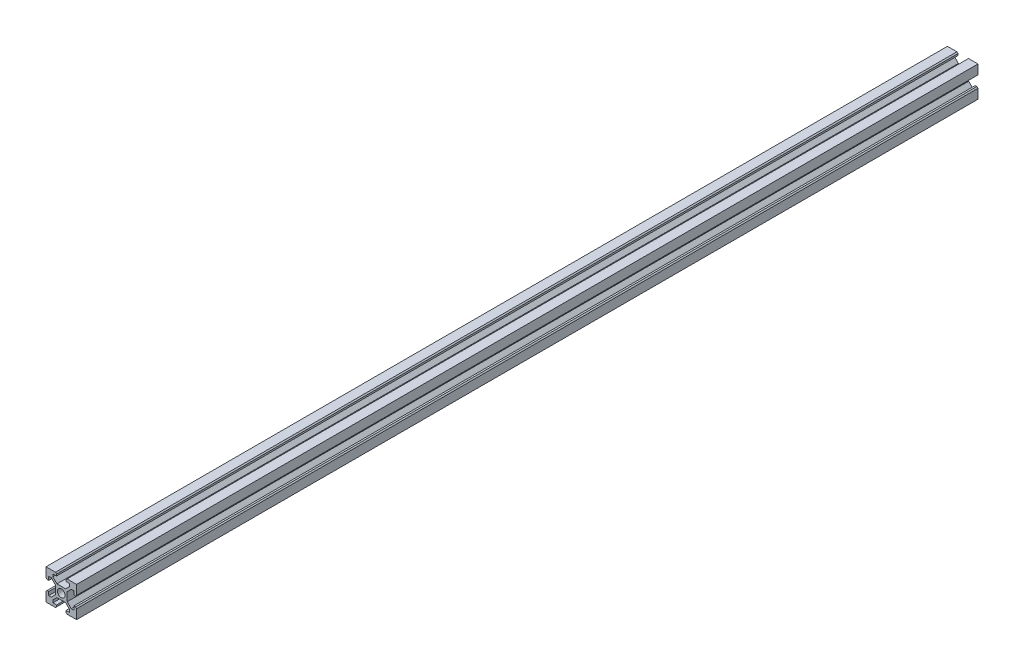
SolidWorks part; units mm, degrees
material "Cast Alloy Steel"
ref_plane "Front Plane" through (0, 0, 0) normal (0, 0, 1) x (1, 0, 0)
ref_plane "Top Plane" through (0, 0, 0) normal (0, 1, 0) x (1, 0, 0)
ref_plane "Right Plane" through (0, 0, 0) normal (1, 0, 0) x (0, 0, -1)
sketch "Sketch1" plane through (0, 0, 0) normal (0, 0, 1) x (1, 0, 0)
  line L0 (3.9, -2.8393) -> (6.5607, -5.5)
  line L1 (-10, 10) -> (10, 10) construction
  line L2 (-10, 10) -> (-10, -10) construction
  line L3 (-10, -10) -> (10, -10) construction
  line L4 (10, 10) -> (10, -10) construction
  line L5 (-10, 10) -> (10, -10) construction
  line L6 (-10, -10) -> (10, 10) construction
  line L7 (-3.9, -3.9) -> (3.9, -3.9) construction
  line L8 (-3.9, -3.9) -> (-3.9, 3.9) construction
  line L9 (-3.9, 3.9) -> (3.9, 3.9) construction
  line L10 (3.9, -3.9) -> (3.9, 3.9) construction
  line L11 (-3.9, -3.9) -> (3.9, 3.9) construction
  line L12 (-3.9, 3.9) -> (3.9, -3.9) construction
  line L13 (-10, 10) -> (-5.5, 10) construction
  line L14 (-10, 10) -> (-10, 5.5) construction
  line L15 (-10, 5.5) -> (-5.5, 5.5) construction
  line L16 (-5.5, 10) -> (-5.5, 5.5) construction
  line L17 (10, 10) -> (5.5, 10) construction
  line L18 (10, 10) -> (10, 5.5) construction
  line L19 (10, 5.5) -> (5.5, 5.5) construction
  line L20 (5.5, 10) -> (5.5, 5.5) construction
  line L21 (-10, -10) -> (-5.5, -10) construction
  line L22 (-10, -10) -> (-10, -5.5) construction
  line L23 (-10, -5.5) -> (-5.5, -5.5) construction
  line L24 (-5.5, -10) -> (-5.5, -5.5) construction
  line L25 (10, -10) -> (5.5, -10) construction
  line L26 (10, -10) -> (10, -5.5) construction
  line L27 (10, -5.5) -> (5.5, -5.5) construction
  line L28 (5.5, -10) -> (5.5, -5.5) construction
  line L29 (2.8393, -3.9) -> (5.5, -6.5607)
  line L30 (-5.5, 6.5607) -> (-2.8393, 3.9)
  line L31 (-6.5607, 5.5) -> (-3.9, 2.8393)
  line L32 (5.5, 6.5607) -> (2.8393, 3.9)
  line L33 (6.5607, 5.5) -> (3.9, 2.8393)
  line L34 (-6.5607, -5.5) -> (-3.9, -2.8393)
  line L35 (-5.5, -6.5607) -> (-2.8393, -3.9)
  line L36 (-2.8393, 3.9) -> (2.8393, 3.9)
  line L37 (-3.9, 2.8393) -> (-3.9, -2.8393)
  line L38 (-2.8393, -3.9) -> (2.8393, -3.9)
  line L39 (3.9, -2.8393) -> (3.9, 2.8393)
  line L40 (5.5, 6.5607) -> (5.5, 8.2007)
  line L41 (5.5, 8.2007) -> (3.1, 8.2007)
  line L42 (3.1, 8.2007) -> (3.1, 9.3)
  line L43 (3.1, 9.3) -> (3.8, 10)
  line L44 (3.8, 10) -> (10, 10)
  line L45 (10, 10) -> (10, 3.8)
  line L46 (10, 3.8) -> (9.3, 3.1)
  line L47 (9.3, 3.1) -> (8.2007, 3.1)
  line L48 (8.2007, 3.1) -> (8.2007, 5.5)
  line L49 (8.2007, 5.5) -> (6.5607, 5.5)
  line L50 (3.1, -8.2007) -> (5.5, -8.2007)
  line L51 (3.1, -9.3) -> (3.1, -8.2007)
  line L52 (3.8, -10) -> (3.1, -9.3)
  line L53 (10, -10) -> (3.8, -10)
  line L54 (10, -3.8) -> (10, -10)
  line L55 (9.3, -3.1) -> (10, -3.8)
  line L56 (8.2007, -3.1) -> (9.3, -3.1)
  line L57 (8.2007, -5.5) -> (8.2007, -3.1)
  line L58 (6.5607, -5.5) -> (8.2007, -5.5)
  line L59 (5.5, -8.2007) -> (5.5, -6.5607)
  line L60 (-8.2007, -3.1) -> (-8.2007, -5.5)
  line L61 (-9.3, -3.1) -> (-8.2007, -3.1)
  line L62 (-10, -3.8) -> (-9.3, -3.1)
  line L63 (-10, -10) -> (-10, -3.8)
  line L64 (-3.8, -10) -> (-10, -10)
  line L65 (-3.1, -9.3) -> (-3.8, -10)
  line L66 (-3.1, -8.2007) -> (-3.1, -9.3)
  line L67 (-5.5, -8.2007) -> (-3.1, -8.2007)
  line L68 (-5.5, -6.5607) -> (-5.5, -8.2007)
  line L69 (-8.2007, -5.5) -> (-6.5607, -5.5)
  line L70 (-3.1, 8.2007) -> (-5.5, 8.2007)
  line L71 (-3.1, 9.3) -> (-3.1, 8.2007)
  line L72 (-3.8, 10) -> (-3.1, 9.3)
  line L73 (-10, 10) -> (-3.8, 10)
  line L74 (-10, 3.8) -> (-10, 10)
  line L75 (-9.3, 3.1) -> (-10, 3.8)
  line L76 (-8.2007, 3.1) -> (-9.3, 3.1)
  line L77 (-8.2007, 5.5) -> (-8.2007, 3.1)
  line L78 (-6.5607, 5.5) -> (-8.2007, 5.5)
  line L79 (-5.5, 8.2007) -> (-5.5, 6.5607)
  circle A0 centre (0, 0) radius 2.5
  point P83 (0, 0)
  dimension "D1" = 5
  dimension "D2" = 20
  dimension "D3" = 7.8
  dimension "D4" = 4.5
  dimension "D5" = 1.5
  dimension "D6" = 0.75
  dimension "D7" = 1.5
  dimension "D8" = 0.75
  dimension "D9" = 1.5
  dimension "D10" = 0.75
  dimension "D11" = 1.5
  dimension "D12" = 0.75
  dimension "D13" = 1.64
  dimension "D14" = 45
  dimension "D15" = 3.1
  dimension "D16" = 6.2
  dimension "D17" = 6.2
  dimension "D18" = 3.1
  dimension "D19" = 4
extrude "Boss-Extrude1" add sketch "Sketch1" along normal mid plane 590 contours L79 L70 L71 L72 L73 L74 L75 L76 L77 L78 L31 L37 L34 L69 L60 L61 L62 L63 L64 L65 L66 L67 L68 L35 L38 L29 L59 L50 L51 L52 L53 L54 L55 L56 L57 L58 L0 L39 L33 L49 L48 L47 L46 L45 L44 L43 L42 L41 L40 L32 L36
